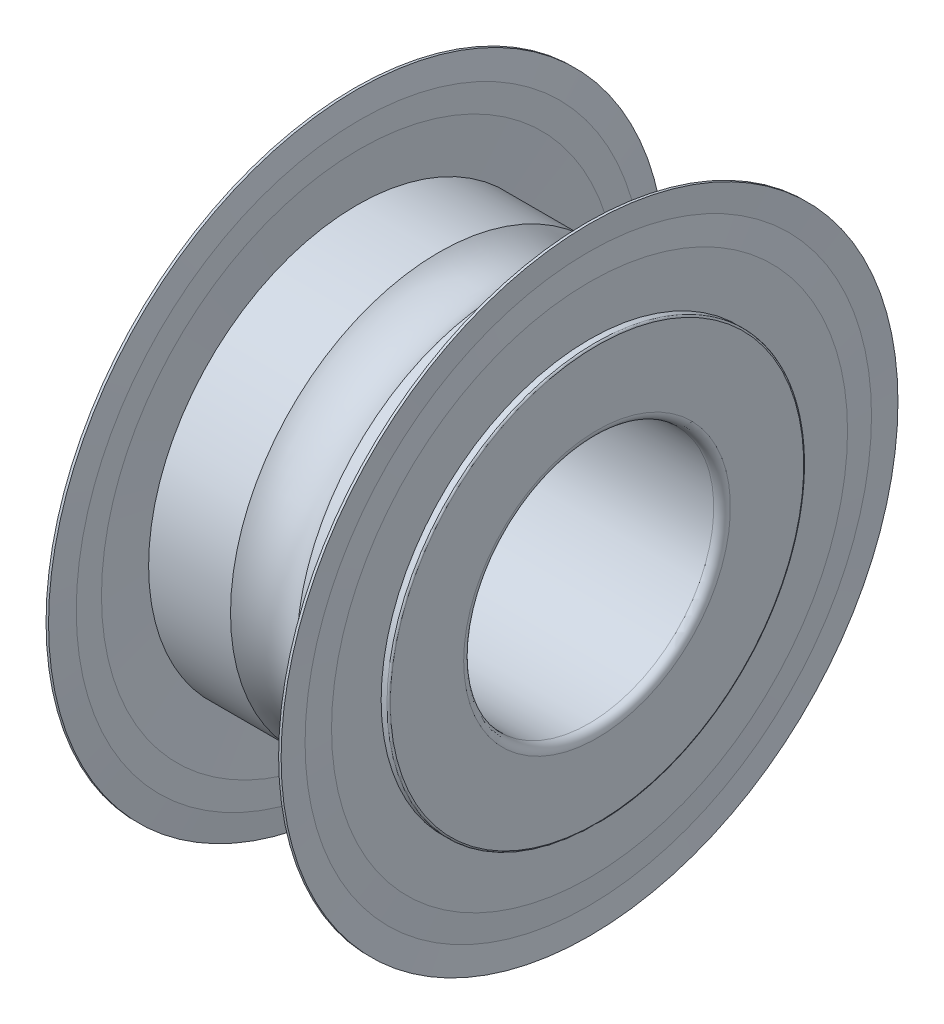
SolidWorks part; units mm, degrees
ref_plane "Ebene vorne" through (0, 0, 0) normal (0, 0, 1) x (1, 0, 0)
ref_plane "Ebene oben" through (0, 0, 0) normal (0, 1, 0) x (1, 0, 0)
ref_plane "Ebene rechts" through (0, 0, 0) normal (1, 0, 0) x (0, 0, -1)
ref_plane "Plane1" through (0, 0, 0) normal (0, 0, 1) x (1, 0, 0)
sketch "Sketch1" plane through (0, 0, 0) normal (0, 0, 1) x (1, 0, 0)
  line L0 (0, 2.48) -> (0, 1.6)
  line L1 (0.1, 1.5) -> (2.9, 1.5)
  line L2 (3, 1.6) -> (3, 2.48)
  line L3 (2.98, 2.5) -> (1.8969, 2.5)
  line L4 (1.1031, 2.5) -> (0.02, 2.5)
  line L5 (50, 0) -> (-50, 0) construction
  arc A0 (0, 1.6) -> (0.1, 1.5) centre (0.1, 1.6) ccw
  arc A1 (2.9, 1.5) -> (3, 1.6) centre (2.9, 1.6) ccw
  arc A2 (3, 2.48) -> (2.98, 2.5) centre (2.98, 2.48) ccw
  arc A3 (1.8969, 2.5) -> (1.1031, 2.5) centre (1.5, 2.95) cw
  arc A4 (0.02, 2.5) -> (0, 2.48) centre (0.02, 2.48) ccw
revolve "Revolve1" add sketch "Sketch1" angle 360 about L5
ref_plane "Plane2" through (0, 0, 0) normal (0, 0, 1) x (1, 0, 0)
sketch "Sketch2" plane through (0, 0, 0) normal (0, 0, 1) x (1, 0, 0)
  line L0 (0.09, 3.7) -> (0.105, 3.3975)
  line L1 (0.105, 3.3975) -> (0.09, 3.095)
  line L2 (0.09, 3.095) -> (0.09, 2.49)
  line L3 (0.09, 2.49) -> (0.12, 2.49)
  line L4 (0.12, 2.49) -> (0.15, 3.095)
  line L5 (0.15, 3.095) -> (0.15, 3.3975)
  line L6 (0.15, 3.3975) -> (0.12, 3.7)
  line L7 (0.12, 3.7) -> (0.09, 3.7)
  line L8 (50, 0) -> (-50, 0) construction
revolve "Revolve2" add sketch "Sketch2" angle 360 about L8
ref_plane "Plane3" through (0, 0, 0) normal (0, 0, 1) x (1, 0, 0)
sketch "Sketch3" plane through (0, 0, 0) normal (0, 0, 1) x (1, 0, 0)
  line L0 (2.85, 3.3975) -> (2.85, 3.095)
  line L1 (2.85, 3.095) -> (2.88, 2.49)
  line L2 (2.88, 2.49) -> (2.91, 2.49)
  line L3 (2.91, 2.49) -> (2.91, 3.095)
  line L4 (2.91, 3.095) -> (2.895, 3.3975)
  line L5 (2.895, 3.3975) -> (2.91, 3.7)
  line L6 (2.91, 3.7) -> (2.88, 3.7)
  line L7 (2.88, 3.7) -> (2.85, 3.3975)
  line L8 (50, 0) -> (-50, 0) construction
revolve "Revolve3" add sketch "Sketch3" angle 360 about L8
